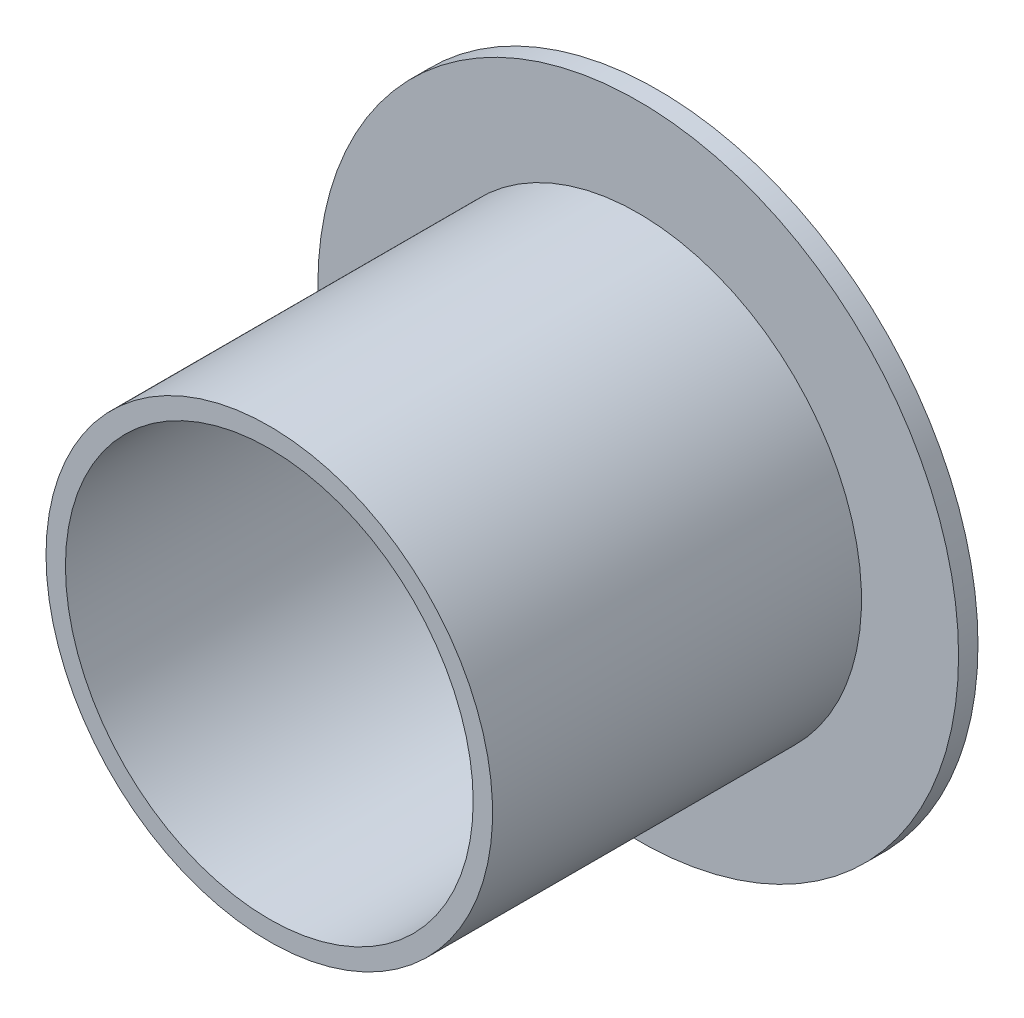
SolidWorks part; units mm, degrees
ref_plane "前视基准面" through (0, 0, 0) normal (0, 0, 1) x (1, 0, 0)
ref_plane "上视基准面" through (0, 0, 0) normal (0, 1, 0) x (1, 0, 0)
ref_plane "右视基准面" through (0, 0, 0) normal (1, 0, 0) x (0, 0, -1)
other "Configuration Table"
sketch "草图1" plane through (0, 0, 0) normal (0, 1, 0) x (1, 0, 0)
  line L0 (0, 0) -> (6, 0)
  line L1 (6, 0) -> (6, -1)
  line L2 (6, -1) -> (1, -1)
  line L3 (1, -1) -> (1, -20)
  line L4 (1, -20) -> (0, -20)
  line L5 (0, -20) -> (0, 0)
  line L6 (-10.5, 0) -> (-10.5, -8.2247) construction
  dimension "D1" = 19
  dimension "D2" = 1
  dimension "D3" = 1
  dimension "D4" = 10.5
  dimension "D5" = 5
revolve "旋转1" add sketch "草图1" angle 360 about L6
